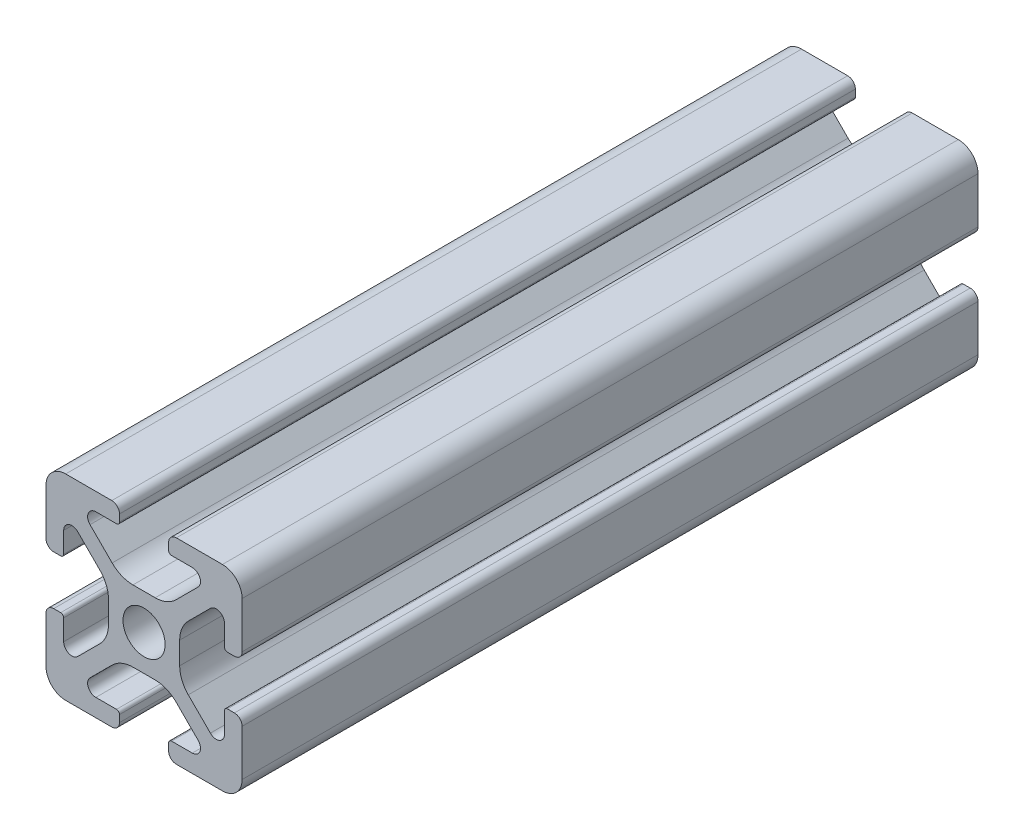
SolidWorks part; units mm, degrees
ref_plane "Front Plane" through (0, 0, 0) normal (0, 0, 1) x (1, 0, 0)
ref_plane "Top Plane" through (0, 0, 0) normal (0, 1, 0) x (1, 0, 0)
ref_plane "Right Plane" through (0, 0, 0) normal (1, 0, 0) x (0, 0, -1)
sketch "Sketch1" plane through (0, 0, 0) normal (0, 0, 1) x (1, 0, 0)
  line L2 (-9.9949, 7.9883) -> (-9.9949, 3.2893)
  line L3 (-7.9883, 9.9949) -> (-3.2893, 9.9949)
  line L4 (-2.5019, 9.2075) -> (-2.5019, 8.4963)
  line L5 (-2.8067, 8.1915) -> (-4.9149, 8.1915)
  line L6 (-5.5076, 6.7606) -> (-3.2528, 4.5058)
  line L7 (-6.7606, 5.5076) -> (-4.5058, 3.2528)
  line L8 (-8.1915, 4.9149) -> (-8.1915, 2.8067)
  line L9 (-8.4963, 2.5019) -> (-9.2075, 2.5019)
  line L11 (-1.1334, 3.6279) -> (1.1334, 3.6279)
  line L12 (-3.6279, 1.1334) -> (-3.6279, -1.1334)
  line L13 (8.4963, 2.5019) -> (9.2075, 2.5019)
  line L14 (8.1915, 4.9149) -> (8.1915, 2.8067)
  line L15 (9.9949, 7.9883) -> (9.9949, 3.2893)
  line L16 (7.9883, 9.9949) -> (3.2893, 9.9949)
  line L17 (2.5019, 9.2075) -> (2.5019, 8.4963)
  line L18 (2.8067, 8.1915) -> (4.9149, 8.1915)
  line L19 (3.6279, 1.1334) -> (3.6279, -1.1334)
  line L20 (5.5076, 6.7606) -> (3.2528, 4.5058)
  line L21 (6.7606, 5.5076) -> (4.5058, 3.2528)
  line L22 (-8.4963, -2.5019) -> (-9.2075, -2.5019)
  line L23 (-8.1915, -4.9149) -> (-8.1915, -2.8067)
  line L24 (-6.7606, -5.5076) -> (-4.5058, -3.2528)
  line L25 (-5.5076, -6.7606) -> (-3.2528, -4.5058)
  line L26 (-2.8067, -8.1915) -> (-4.9149, -8.1915)
  line L27 (-2.5019, -9.2075) -> (-2.5019, -8.4963)
  line L28 (-7.9883, -9.9949) -> (-3.2893, -9.9949)
  line L29 (-9.9949, -7.9883) -> (-9.9949, -3.2893)
  line L30 (9.9949, -7.9883) -> (9.9949, -3.2893)
  line L31 (7.9883, -9.9949) -> (3.2893, -9.9949)
  line L32 (2.5019, -9.2075) -> (2.5019, -8.4963)
  line L33 (2.8067, -8.1915) -> (4.9149, -8.1915)
  line L34 (5.5076, -6.7606) -> (3.2528, -4.5058)
  line L35 (6.7606, -5.5076) -> (4.5058, -3.2528)
  line L36 (8.1915, -4.9149) -> (8.1915, -2.8067)
  line L37 (8.4963, -2.5019) -> (9.2075, -2.5019)
  line L38 (-1.1334, -3.6279) -> (1.1334, -3.6279)
  circle A0 centre (0, 0) radius 2.1463
  arc A1 (-9.9949, 7.9883) -> (-7.9883, 9.9949) centre (-7.9883, 7.9883) cw
  arc A2 (-6.7606, 5.5076) -> (-8.1915, 4.9149) centre (-7.3533, 4.9149) ccw
  arc A3 (-4.9149, 8.1915) -> (-5.5076, 6.7606) centre (-4.9149, 7.3533) ccw
  arc A4 (-3.2893, 9.9949) -> (-2.5019, 9.2075) centre (-3.2893, 9.2075) cw
  arc A5 (-9.9949, 3.2893) -> (-9.2075, 2.5019) centre (-9.2075, 3.2893) ccw
  arc A6 (-8.1915, 2.8067) -> (-8.4963, 2.5019) centre (-8.4963, 2.8067) cw
  arc A7 (-2.5019, 8.4963) -> (-2.8067, 8.1915) centre (-2.8067, 8.4963) cw
  arc A8 (-1.1334, 3.6279) -> (-3.2528, 4.5058) centre (-1.1334, 6.6251) cw
  arc A9 (-3.6279, 1.1334) -> (-4.5058, 3.2528) centre (-6.6251, 1.1334) ccw
  arc A10 (8.1915, 2.8067) -> (8.4963, 2.5019) centre (8.4963, 2.8067) ccw
  arc A11 (9.9949, 3.2893) -> (9.2075, 2.5019) centre (9.2075, 3.2893) cw
  arc A12 (9.9949, 7.9883) -> (7.9883, 9.9949) centre (7.9883, 7.9883) ccw
  arc A13 (3.2893, 9.9949) -> (2.5019, 9.2075) centre (3.2893, 9.2075) ccw
  arc A14 (2.5019, 8.4963) -> (2.8067, 8.1915) centre (2.8067, 8.4963) ccw
  arc A15 (1.1334, 3.6279) -> (3.2528, 4.5058) centre (1.1334, 6.6251) ccw
  arc A16 (3.6279, 1.1334) -> (4.5058, 3.2528) centre (6.6251, 1.1334) cw
  arc A17 (6.7606, 5.5076) -> (8.1915, 4.9149) centre (7.3533, 4.9149) cw
  arc A18 (4.9149, 8.1915) -> (5.5076, 6.7606) centre (4.9149, 7.3533) cw
  arc A19 (-3.6279, -1.1334) -> (-4.5058, -3.2528) centre (-6.6251, -1.1334) cw
  arc A20 (-1.1334, -3.6279) -> (-3.2528, -4.5058) centre (-1.1334, -6.6251) ccw
  arc A21 (-2.5019, -8.4963) -> (-2.8067, -8.1915) centre (-2.8067, -8.4963) ccw
  arc A22 (-8.1915, -2.8067) -> (-8.4963, -2.5019) centre (-8.4963, -2.8067) ccw
  arc A23 (-9.9949, -3.2893) -> (-9.2075, -2.5019) centre (-9.2075, -3.2893) cw
  arc A24 (-3.2893, -9.9949) -> (-2.5019, -9.2075) centre (-3.2893, -9.2075) ccw
  arc A25 (-4.9149, -8.1915) -> (-5.5076, -6.7606) centre (-4.9149, -7.3533) cw
  arc A26 (-6.7606, -5.5076) -> (-8.1915, -4.9149) centre (-7.3533, -4.9149) cw
  arc A27 (-9.9949, -7.9883) -> (-7.9883, -9.9949) centre (-7.9883, -7.9883) ccw
  arc A28 (9.9949, -7.9883) -> (7.9883, -9.9949) centre (7.9883, -7.9883) cw
  arc A29 (6.7606, -5.5076) -> (8.1915, -4.9149) centre (7.3533, -4.9149) ccw
  arc A30 (4.9149, -8.1915) -> (5.5076, -6.7606) centre (4.9149, -7.3533) ccw
  arc A31 (3.2893, -9.9949) -> (2.5019, -9.2075) centre (3.2893, -9.2075) cw
  arc A32 (9.9949, -3.2893) -> (9.2075, -2.5019) centre (9.2075, -3.2893) ccw
  arc A33 (8.1915, -2.8067) -> (8.4963, -2.5019) centre (8.4963, -2.8067) cw
  arc A34 (2.5019, -8.4963) -> (2.8067, -8.1915) centre (2.8067, -8.4963) cw
  arc A35 (1.1334, -3.6279) -> (3.2528, -4.5058) centre (1.1334, -6.6251) cw
  arc A36 (3.6279, -1.1334) -> (4.5058, -3.2528) centre (6.6251, -1.1334) ccw
extrude "Boss-Extrude1" add sketch "Sketch1" along normal mid plane 75
